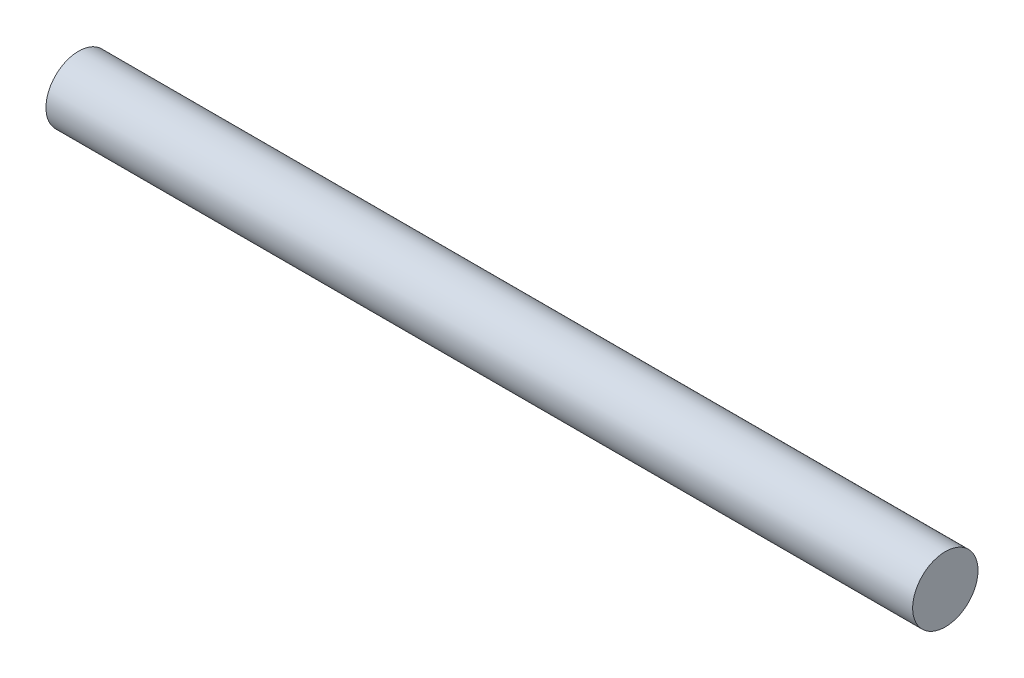
SolidWorks part; units mm, degrees
ref_plane "Front Plane" through (0, 0, 0) normal (0, 0, 1) x (1, 0, 0)
ref_plane "Top Plane" through (0, 0, 0) normal (0, 1, 0) x (1, 0, 0)
ref_plane "Right Plane" through (0, 0, 0) normal (1, 0, 0) x (0, 0, -1)
sketch "Sketch1" plane through (0, 0, 0) normal (1, 0, 0) x (0, 0, -1)
  circle A0 centre (0, 0) radius 19.05
  dimension "D1" = 38.1
extrude "Boss-Extrude1" add sketch "Sketch1" along normal blind 505.54
sketch "Sketch2" plane through (505.54, 0, 0) normal (1, 0, 0) x (0, 0, -1)
  circle A1 centre (0, 0) radius 19.05
  circle A2 centre (0, 0) radius 19.05
  dimension "D1" = 0
curve "Helix/Spiral1" pitch 19.05 height 400 turns 20.9974
sketch "Sketch3" plane through (0, 0, 0) normal (0, 0, 1) x (1, 0, 0)
  circle A0 centre (505.54, -19.05) radius 3
  dimension "D1" = 6
